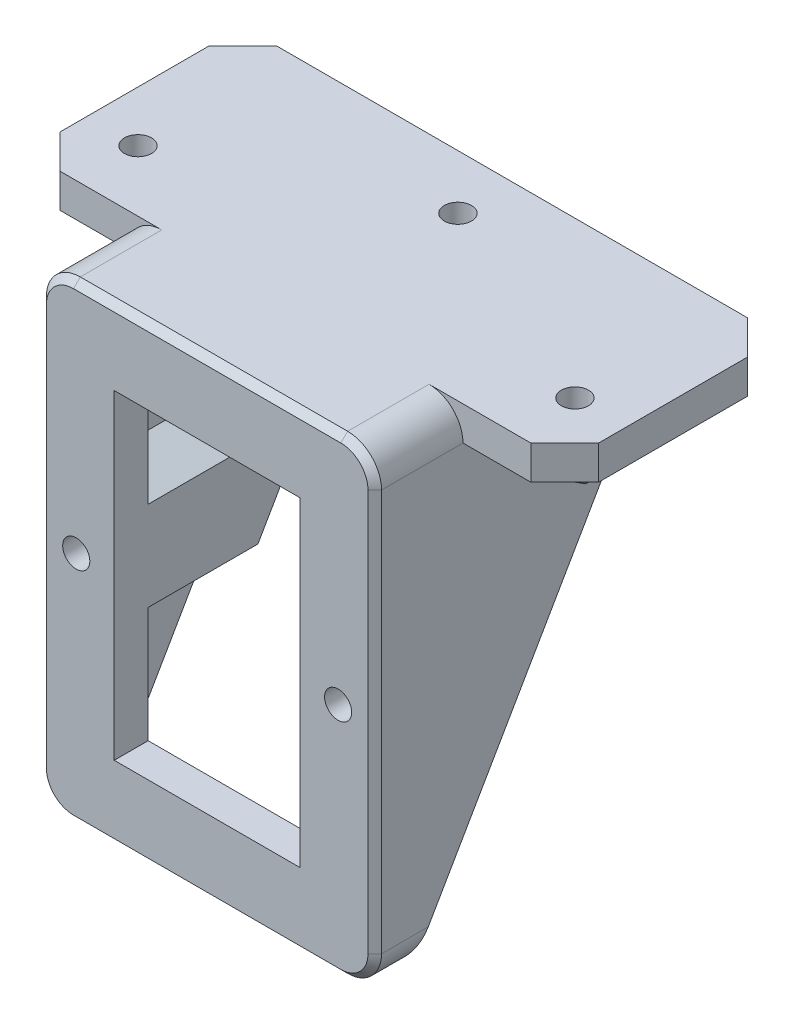
SolidWorks part; units mm, degrees
ref_plane "Front Plane" through (0, 0, 0) normal (0, 0, 1) x (1, 0, 0)
ref_plane "Top Plane" through (0, 0, 0) normal (0, 1, 0) x (1, 0, 0)
ref_plane "Right Plane" through (0, 0, 0) normal (1, 0, 0) x (0, 0, -1)
sketch "Sketch1" plane through (0, 0, 0) normal (0, 0, 1) x (1, 0, 0)
  line L0 (-36.4532, 0) -> (46.6601, 0) construction
  line L1 (-13.5, 23.4) -> (13.5, 23.4) construction
  line L2 (-13.5, 23.4) -> (-13.5, -23.4) construction
  line L3 (-13.5, -23.4) -> (13.5, -23.4) construction
  line L4 (13.5, 23.4) -> (13.5, -23.4) construction
  line L5 (0, 29.9068) -> (0, -40.6544) construction
  line L6 (-13.7, 23.6) -> (13.7, 23.6)
  line L7 (13.7, 23.6) -> (13.7, -23.6)
  line L8 (-13.7, -23.6) -> (13.7, -23.6)
  line L9 (-13.7, 23.6) -> (-13.7, -23.6)
  line L10 (-24.7, 34.6) -> (-24.7, -34.6)
  line L11 (-24.7, -34.6) -> (24.7, -34.6)
  line L12 (24.7, 34.6) -> (24.7, -34.6)
  line L13 (-24.7, 34.6) -> (24.7, 34.6)
  dimension "D1" = 46.8
  dimension "D2" = 27
  dimension "D3" = 0.2
  dimension "D4" = 11
extrude "Boss-Extrude1" add sketch "Sketch1" against normal blind 5
sketch "Sketch2" plane through (0, 0, 0) normal (0, 0, 1) x (1, 0, 0)
  line L0 (13.7, -23.6) -> (13.7, 23.6) construction
  line L1 (0, 0) -> (0, 17.0969) construction
  circle A0 centre (19.3, 0) radius 2
  circle A1 centre (-19.3, 0) radius 2
  dimension "D1" = 4
  dimension "D2" = 5.6
extrude "Cut-Extrude1" cut sketch "Sketch2" against normal blind 15
sketch "Sketch4" plane through (24.7, 0, 0) normal (1, 0, 0) x (0, 0, -1)
  line L0 (5, 34.6) -> (44.9526, 34.6)
  line L4 (44.9526, 34.6) -> (5, -34.6)
  line L5 (5, -34.6) -> (5, 34.6) construction
  line L6 (5, -34.6) -> (5, 34.6)
  line L7 (5, -34.6) -> (0, -34.6) construction
  dimension "D1" = 30
extrude "Boss-Extrude2" add sketch "Sketch4" against normal up to vertex (49.4 mm away)
sketch "Sketch3" plane through (0, 0, -5) normal (0, 0, -1) x (-1, 0, 0)
  line L1 (-19.3, -4.0415) -> (-15.8, -2.0207)
  line L2 (-15.8, -2.0207) -> (-15.8, 2.0207)
  line L3 (-15.8, 2.0207) -> (-19.3, 4.0415)
  line L4 (-19.3, 4.0415) -> (-22.8, 2.0207)
  line L5 (-22.8, 2.0207) -> (-22.8, -2.0207)
  line L6 (-22.8, -2.0207) -> (-19.3, -4.0415)
  line L7 (19.3, -4.0415) -> (22.8, -2.0207)
  line L8 (22.8, -2.0207) -> (22.8, 2.0207)
  line L9 (22.8, 2.0207) -> (19.3, 4.0415)
  line L10 (19.3, 4.0415) -> (15.8, 2.0207)
  line L11 (15.8, 2.0207) -> (15.8, -2.0207)
  line L12 (15.8, -2.0207) -> (19.3, -4.0415)
  circle A0 centre (-19.3, 0) radius 3.5 construction
  circle A1 centre (19.3, 0) radius 3.5 construction
  dimension "D1" = 7
extrude "Cut-Extrude2" cut sketch "Sketch3" along normal through all
sketch "Sketch5" plane through (0, 0, -5) normal (0, 0, 1) x (1, 0, 0)
  line L4 (-13.7, 23.6) -> (-13.7, -23.6)
  line L5 (-13.7, -23.6) -> (13.7, -23.6)
  line L6 (13.7, -23.6) -> (13.7, 23.6)
  line L7 (13.7, 23.6) -> (-13.7, 23.6)
  line L8 (-13.7, 23.6) -> (-13.7, -23.6)
  line L9 (-13.7, -23.6) -> (13.7, -23.6)
  line L10 (13.7, -23.6) -> (13.7, 23.6)
  line L11 (13.7, 23.6) -> (-13.7, 23.6)
  dimension "D1" = 0
extrude "Cut-Extrude3" cut sketch "Sketch5" against normal blind 93
sketch "Sketch6" plane through (0, 0, 0) normal (0, 0, 1) x (1, 0, 0)
  line L0 (19.7, 29.6) -> (-19.7, 29.6)
  line L1 (-19.7, 29.6) -> (-19.7, 10.0459)
  line L2 (-19.7, -34.6) -> (19.7, -34.6)
  line L3 (19.7, -34.6) -> (19.7, -10.0459)
  line L4 (24.7, 34.6) -> (-24.7, 34.6)
  line L5 (-24.7, 34.6) -> (-24.7, -34.6)
  line L6 (-24.7, -34.6) -> (24.7, -34.6)
  line L7 (24.7, -34.6) -> (24.7, 34.6)
  line L8 (24.7, 34.6) -> (-24.7, 34.6) construction
  line L10 (-24.7, -34.6) -> (24.7, -34.6) construction
  line L11 (24.7, -6.6973) -> (24.7, 34.6) construction
  line L12 (-15.8, -2.0207) -> (-19.3, -4.0415) construction
  line L13 (-19.3, -4.0415) -> (-22.8, -2.0207) construction
  line L14 (-22.8, -2.0207) -> (-22.8, 2.0207) construction
  line L15 (-22.8, 2.0207) -> (-19.3, 4.0415) construction
  line L16 (-19.3, 4.0415) -> (-15.8, 2.0207) construction
  line L17 (-15.8, 2.0207) -> (-15.8, -2.0207) construction
  line L18 (22.8, -2.0207) -> (19.3, -4.0415) construction
  line L19 (19.3, -4.0415) -> (15.8, -2.0207) construction
  line L20 (15.8, -2.0207) -> (15.8, 2.0207) construction
  line L21 (15.8, 2.0207) -> (19.3, 4.0415) construction
  line L22 (19.3, 4.0415) -> (22.8, 2.0207) construction
  line L23 (22.8, 2.0207) -> (22.8, -2.0207) construction
  line L24 (-15.8, -2.0207) -> (-19.3, -4.0415) construction
  line L25 (-19.3, -4.0415) -> (-22.8, -2.0207) construction
  line L26 (-22.8, -2.0207) -> (-22.8, 2.0207) construction
  line L27 (-22.8, 2.0207) -> (-19.3, 4.0415) construction
  line L28 (-19.3, 4.0415) -> (-15.8, 2.0207) construction
  line L29 (-15.8, 2.0207) -> (-15.8, -2.0207) construction
  line L30 (22.8, -2.0207) -> (19.3, -4.0415) construction
  line L31 (19.3, -4.0415) -> (15.8, -2.0207) construction
  line L32 (15.8, -2.0207) -> (15.8, 2.0207) construction
  line L33 (15.8, 2.0207) -> (19.3, 4.0415) construction
  line L34 (19.3, 4.0415) -> (22.8, 2.0207) construction
  line L35 (22.8, 2.0207) -> (22.8, -2.0207) construction
  line L36 (-19.7, 10.0459) -> (-10.8, 4.9075)
  line L37 (-10.8, 4.9075) -> (-10.8, -4.9075)
  line L38 (-10.8, -4.9075) -> (-19.7, -10.0459)
  line L39 (19.3, 9.815) -> (27.8, 4.9075) construction
  line L40 (19.7, 10.0459) -> (19.7, 29.6)
  line L41 (19.7, -29.6) -> (19.7, 29.6) construction
  line L42 (10.8, 4.9075) -> (19.7, 10.0459)
  line L43 (19.3, -9.815) -> (10.8, -4.9075) construction
  line L46 (19.7, -10.0459) -> (10.8, -4.9075)
  line L47 (10.8, -4.9075) -> (10.8, 4.9075)
  line L48 (-19.7, -10.0459) -> (-19.7, -34.6)
  line L49 (-19.7, 29.6) -> (-19.7, -29.6) construction
  line L50 (-10.8, -4.9075) -> (-19.3, -9.815) construction
  line L51 (-27.8, 4.9075) -> (-19.3, 9.815) construction
  line L52 (-19.3, 9.815) -> (-10.8, 4.9075) construction
  line L53 (-19.3, -9.815) -> (-27.8, -4.9075) construction
  line L54 (10.8, 4.9075) -> (19.3, 9.815) construction
  line L55 (-24.7, 34.6) -> (-24.7, -34.6) construction
  line L56 (-27.8, -4.9075) -> (-27.8, 4.9075) construction
  line L58 (27.8, -4.9075) -> (19.3, -9.815) construction
  line L60 (24.7, -34.6) -> (24.7, 34.6) construction
  line L61 (27.8, 4.9075) -> (27.8, -4.9075) construction
  line L62 (-19.7, -29.6) -> (19.7, -29.6) construction
  dimension "D1" = 0
  dimension "D2" = 5
  dimension "D3" = 5
  dimension "D4" = 5
extrude "Cut-Extrude4" cut sketch "Sketch6" against normal blind 93 from offset 5 offset against normal yes
sketch "Sketch7" plane through (0, 34.6, 0) normal (0, 1, 0) x (1, 0, 0)
  line L0 (24.7, 0) -> (-24.7, 0) construction
  line L1 (-39.7, 44.9526) -> (39.7, 44.9526)
  line L2 (-39.7, 44.9526) -> (-39.7, 0)
  line L3 (-39.7, 0) -> (39.7, 0)
  line L4 (39.7, 44.9526) -> (39.7, 0)
  line L5 (-24.7, 44.9526) -> (24.7, 44.9526) construction
  line L6 (-24.7, 44.9526) -> (-24.7, 0) construction
  line L8 (0, 0) -> (0, 55.3404) construction
  dimension "D1" = 15
extrude "Boss-Extrude3" add sketch "Sketch7" against normal blind 5
sketch "Sketch8" plane through (0, 29.6, 0) normal (0, -1, 0) x (1, 0, 0)
  line L1 (-3.5, -34.9319) -> (-3.5, -38.9734)
  line L2 (-3.5, -38.9734) -> (0, -40.9941)
  line L3 (0, -40.9941) -> (3.5, -38.9734)
  line L4 (3.5, -38.9734) -> (3.5, -34.9319)
  line L5 (3.5, -34.9319) -> (0, -32.9112)
  line L6 (0, -32.9112) -> (-3.5, -34.9319)
  line L7 (-32.2, -17.9585) -> (-35.7, -19.9793)
  line L8 (-35.7, -19.9793) -> (-35.7, -24.0207)
  line L9 (-35.7, -24.0207) -> (-32.2, -26.0415)
  line L10 (-32.2, -26.0415) -> (-28.7, -24.0207)
  line L11 (-28.7, -24.0207) -> (-28.7, -19.9793)
  line L12 (-28.7, -19.9793) -> (-32.2, -17.9585)
  line L13 (32.2, -17.9585) -> (28.7, -19.9793)
  line L14 (28.7, -19.9793) -> (28.7, -24.0207)
  line L15 (28.7, -24.0207) -> (32.2, -26.0415)
  line L16 (32.2, -26.0415) -> (35.7, -24.0207)
  line L17 (35.7, -24.0207) -> (35.7, -19.9793)
  line L18 (35.7, -19.9793) -> (32.2, -17.9585)
  line L30 (25.7, -25.7528) -> (32.2, -29.5056)
  line L31 (32.2, -29.5056) -> (38.7, -25.7528)
  line L32 (38.7, -25.7528) -> (38.7, -18.2472)
  line L33 (38.7, -18.2472) -> (32.2, -14.4944)
  line L34 (32.2, -14.4944) -> (25.7, -18.2472)
  line L35 (25.7, -18.2472) -> (25.7, -25.7528)
  line L36 (32.2, 0) -> (32.2, -44.9526) construction
  line L37 (24.7, 0) -> (39.7, 0) construction
  line L38 (39.7, -44.9526) -> (-39.7, -44.9526) construction
  line L39 (0, 0) -> (0, -56.5255) construction
  line L40 (-39.7, 0) -> (-24.7, 0) construction
  line L41 (-32.2, -14.4944) -> (-38.7, -18.2472)
  line L42 (-38.7, -18.2472) -> (-38.7, -25.7528)
  line L43 (-38.7, -25.7528) -> (-32.2, -29.5056)
  line L44 (-32.2, -29.5056) -> (-25.7, -25.7528)
  line L45 (-25.7, -25.7528) -> (-25.7, -18.2472)
  line L46 (-25.7, -18.2472) -> (-32.2, -14.4944)
  line L47 (0, -29.4471) -> (-6.5, -33.1999)
  line L48 (-6.5, -33.1999) -> (-6.5, -40.7054)
  line L49 (-6.5, -40.7054) -> (0, -44.4582)
  line L50 (0, -44.4582) -> (6.5, -40.7054)
  line L51 (6.5, -40.7054) -> (6.5, -33.1999)
  line L52 (6.5, -33.1999) -> (0, -29.4471)
  circle A0 centre (0, -36.9526) radius 3.5 construction
  circle A1 centre (-32.2, -22) radius 3.5 construction
  circle A2 centre (32.2, -22) radius 3.5 construction
  circle A3 centre (-32.2, -22) radius 6.5 construction
  circle A4 centre (0, -36.9526) radius 6.5 construction
  point P55 (-32.2, 0)
  dimension "D1" = 7
  dimension "D5" = 3
  dimension "D3" = 22
  dimension "D4" = 8
  dimension "D2" = 3
extrude "Boss-Extrude4" add sketch "Sketch8" along normal blind 3
sketch "Sketch9" plane through (0, 29.6, 0) normal (0, -1, 0) x (1, 0, 0)
  line L0 (3.5, -34.9319) -> (0, -32.9112) construction
  line L1 (0, -32.9112) -> (-3.5, -34.9319) construction
  line L2 (-3.5, -34.9319) -> (-3.5, -38.9734) construction
  line L3 (-3.5, -38.9734) -> (0, -40.9941) construction
  line L4 (0, -40.9941) -> (3.5, -38.9734) construction
  line L5 (3.5, -38.9734) -> (3.5, -34.9319) construction
  line L6 (35.7, -24.0207) -> (35.7, -19.9793)
  line L7 (35.7, -19.9793) -> (32.2, -17.9585)
  line L8 (32.2, -17.9585) -> (28.7, -19.9793)
  line L9 (28.7, -19.9793) -> (28.7, -24.0207)
  line L10 (28.7, -24.0207) -> (32.2, -26.0415)
  line L11 (32.2, -26.0415) -> (35.7, -24.0207)
  line L12 (35.7, -24.0207) -> (35.7, -19.9793)
  line L13 (35.7, -19.9793) -> (32.2, -17.9585)
  line L14 (32.2, -17.9585) -> (28.7, -19.9793)
  line L15 (28.7, -19.9793) -> (28.7, -24.0207)
  line L16 (28.7, -24.0207) -> (32.2, -26.0415)
  line L17 (32.2, -26.0415) -> (35.7, -24.0207)
  line L18 (-28.7, -24.0207) -> (-28.7, -19.9793) construction
  line L19 (-28.7, -19.9793) -> (-32.2, -17.9585) construction
  line L20 (-32.2, -17.9585) -> (-35.7, -19.9793) construction
  line L21 (-35.7, -19.9793) -> (-35.7, -24.0207) construction
  line L22 (-35.7, -24.0207) -> (-32.2, -26.0415) construction
  line L23 (-32.2, -26.0415) -> (-28.7, -24.0207) construction
  line L24 (3.5, -34.9319) -> (0, -32.9112)
  line L25 (0, -32.9112) -> (-3.5, -34.9319)
  line L26 (-3.5, -34.9319) -> (-3.5, -38.9734)
  line L27 (-3.5, -38.9734) -> (0, -40.9941)
  line L28 (0, -40.9941) -> (3.5, -38.9734)
  line L29 (3.5, -38.9734) -> (3.5, -34.9319)
  line L30 (-28.7, -24.0207) -> (-28.7, -19.9793)
  line L31 (-28.7, -19.9793) -> (-32.2, -17.9585)
  line L32 (-32.2, -17.9585) -> (-35.7, -19.9793)
  line L33 (-35.7, -19.9793) -> (-35.7, -24.0207)
  line L34 (-35.7, -24.0207) -> (-32.2, -26.0415)
  line L35 (-32.2, -26.0415) -> (-28.7, -24.0207)
  dimension "D1" = 0
extrude "Cut-Extrude5" cut sketch "Sketch9" against normal blind 1
sketch "Sketch10" plane through (0, 30.6, 0) normal (0, -1, 0) x (1, 0, 0)
  line L0 (24.7, 0) -> (39.7, 0) construction
  line L1 (-3.5, -34.9319) -> (-3.5, -38.9734) construction
  line L2 (-35.7, -19.9793) -> (-35.7, -24.0207) construction
  circle A0 centre (32.2, -22) radius 2
  circle A1 centre (0, -36.9526) radius 2
  circle A2 centre (-32.2, -22) radius 2
  point P4 (32.2, 0)
  point P9 (-3.5, -36.9526)
  point P16 (-35.7, -22)
  dimension "D1" = 4
  dimension "D2" = 22
extrude "Cut-Extrude6" cut sketch "Sketch10" against normal through all
sketch "Sketch11" plane through (0, 0, 0) normal (0, 0, 1) x (1, 0, 0)
  line L0 (39.7, 34.6) -> (-39.7, 34.6) construction
  line L1 (24.7, 29.6) -> (39.7, 29.6)
  line L2 (24.7, 29.6) -> (24.7, 34.6)
  line L3 (24.7, 34.6) -> (39.7, 34.6)
  line L4 (39.7, 29.6) -> (39.7, 34.6)
  line L5 (-24.7, 29.6) -> (-39.7, 29.6)
  line L6 (-24.7, 29.6) -> (-24.7, 34.6)
  line L7 (-24.7, 34.6) -> (-39.7, 34.6)
  line L8 (-39.7, 29.6) -> (-39.7, 34.6)
  line L9 (-39.7, 29.6) -> (-39.7, 34.6) construction
extrude "Cut-Extrude7" cut sketch "Sketch11" against normal blind 13
chamfer "Chamfer1" distance 2.75 angle 45 18 edges at (-25.7, 26.6, -22) (-28.95, 26.6, -27.6292) (-35.45, 26.6, -27.6292) (-38.7, 26.6, -22) (-35.45, 26.6, -16.3708) (-28.95, 26.6, -16.3708) (6.5, 26.6, -36.9526) (3.25, 26.6, -42.5818) (-3.25, 26.6, -42.5818) (-6.5, 26.6, -36.9526) (-3.25, 26.6, -31.3235) (3.25, 26.6, -31.3235) (28.95, 26.6, -16.3708) (35.45, 26.6, -16.3708) (38.7, 26.6, -22) (35.45, 26.6, -27.6292) (28.95, 26.6, -27.6292) (25.7, 26.6, -22)
sketch "Sketch12" plane through (0, 26.6, 0) normal (0, -1, 0) x (1, 0, 0)
  line L21 (3.5, -38.9734) -> (3.5, -34.9319) construction
  line L22 (3.5, -34.9319) -> (0, -32.9112) construction
  line L23 (0, -32.9112) -> (-3.5, -34.9319) construction
  line L24 (-3.5, -34.9319) -> (-3.5, -38.9734) construction
  line L25 (-3.5, -38.9734) -> (0, -40.9941) construction
  line L26 (0, -40.9941) -> (3.5, -38.9734) construction
  line L27 (35.45, -20.1236) -> (32.2, -18.2472)
  line L28 (32.2, -18.2472) -> (28.95, -20.1236)
  line L29 (28.95, -20.1236) -> (28.95, -23.8764)
  line L30 (28.95, -23.8764) -> (32.2, -25.7528)
  line L31 (35.45, -23.8764) -> (35.45, -20.1236)
  line L32 (32.2, -25.7528) -> (35.45, -23.8764)
  line L33 (35.45, -20.1236) -> (32.2, -18.2472)
  line L34 (32.2, -18.2472) -> (28.95, -20.1236)
  line L35 (28.95, -20.1236) -> (28.95, -23.8764)
  line L36 (28.95, -23.8764) -> (32.2, -25.7528)
  line L37 (35.45, -23.8764) -> (35.45, -20.1236)
  line L38 (32.2, -25.7528) -> (35.45, -23.8764)
  line L39 (32.2, -26.0415) -> (35.7, -24.0207)
  line L40 (35.7, -24.0207) -> (35.7, -19.9793)
  line L41 (35.7, -19.9793) -> (32.2, -17.9585)
  line L42 (32.2, -17.9585) -> (28.7, -19.9793)
  line L43 (28.7, -19.9793) -> (28.7, -24.0207)
  line L44 (28.7, -24.0207) -> (32.2, -26.0415)
  line L45 (32.2, -26.0415) -> (35.7, -24.0207)
  line L46 (35.7, -24.0207) -> (35.7, -19.9793)
  line L47 (35.7, -19.9793) -> (32.2, -17.9585)
  line L48 (32.2, -17.9585) -> (28.7, -19.9793)
  line L49 (28.7, -19.9793) -> (28.7, -24.0207)
  line L50 (28.7, -24.0207) -> (32.2, -26.0415)
  line L51 (-32.2, -26.0415) -> (-28.7, -24.0207) construction
  line L52 (-28.7, -24.0207) -> (-28.7, -19.9793) construction
  line L53 (-28.7, -19.9793) -> (-32.2, -17.9585) construction
  line L54 (-32.2, -17.9585) -> (-35.7, -19.9793) construction
  line L55 (-35.7, -19.9793) -> (-35.7, -24.0207) construction
  line L56 (-35.7, -24.0207) -> (-32.2, -26.0415) construction
  line L57 (3.5, -38.9734) -> (3.5, -34.9319)
  line L58 (3.5, -34.9319) -> (0, -32.9112)
  line L59 (0, -32.9112) -> (-3.5, -34.9319)
  line L60 (-3.5, -34.9319) -> (-3.5, -38.9734)
  line L61 (-3.5, -38.9734) -> (0, -40.9941)
  line L62 (0, -40.9941) -> (3.5, -38.9734)
  line L63 (-32.2, -26.0415) -> (-28.7, -24.0207)
  line L64 (-28.7, -24.0207) -> (-28.7, -19.9793)
  line L65 (-28.7, -19.9793) -> (-32.2, -17.9585)
  line L66 (-32.2, -17.9585) -> (-35.7, -19.9793)
  line L67 (-35.7, -19.9793) -> (-35.7, -24.0207)
  line L68 (-35.7, -24.0207) -> (-32.2, -26.0415)
  line L69 (-3.25, -38.829) -> (0, -40.7054)
  line L70 (0, -40.7054) -> (3.25, -38.829)
  line L71 (3.25, -38.829) -> (3.25, -35.0763)
  line L72 (3.25, -35.0763) -> (0, -33.1999)
  line L73 (0, -33.1999) -> (-3.25, -35.0763)
  line L74 (-3.25, -35.0763) -> (-3.25, -38.829)
  line L75 (-35.45, -23.8764) -> (-32.2, -25.7528)
  line L76 (-32.2, -25.7528) -> (-28.95, -23.8764)
  line L77 (-28.95, -23.8764) -> (-28.95, -20.1236)
  line L78 (-28.95, -20.1236) -> (-32.2, -18.2472)
  line L79 (-32.2, -18.2472) -> (-35.45, -20.1236)
  line L80 (-35.45, -20.1236) -> (-35.45, -23.8764)
  dimension "D1" = 0.25
  dimension "D2" = 0
  dimension "D3" = 0.25
  dimension "D4" = 0.25
extrude "Boss-Extrude5" add sketch "Sketch12" against normal blind 0.5
chamfer "Chamfer2" distance 0.25 angle 45 18 edges at (33.825, 26.6, -19.1854) (30.575, 26.6, -19.1854) (28.95, 26.6, -22) (30.575, 26.6, -24.8146) (33.825, 26.6, -24.8146) (35.45, 26.6, -22) (-33.825, 26.6, -24.8146) (-30.575, 26.6, -24.8146) (-28.95, 26.6, -22) (-30.575, 26.6, -19.1854) (-33.825, 26.6, -19.1854) (-35.45, 26.6, -22) (-1.625, 26.6, -39.7672) (1.625, 26.6, -39.7672) (3.25, 26.6, -36.9526) (1.625, 26.6, -34.1381) (-1.625, 26.6, -34.1381) (-3.25, 26.6, -36.9526)
fillet "Fillet1" radius 5 4 edges at (24.7, -34.6, -2.5) (-24.7, -34.6, -2.5) (-24.7, 34.6, -6.5) (24.7, 34.6, -6.5)
chamfer "Chamfer3" distance 1 angle 45 8 edges at (24.7, 0, 0) (0, -34.6, 0) (-24.7, 0, 0) (0, 34.6, 0) (-23.2355, -33.1355, 0) (-23.2355, 33.1355, 0) (23.2355, 33.1355, 0) (23.2355, -33.1355, 0)
chamfer "Chamfer4" distance 5 angle 45 4 edges at (-39.7, 32.1, -44.9526) (-39.7, 32.1, -13) (39.7, 32.1, -44.9526) (39.7, 32.1, -13)
equation "\"D5@Sketch8\"=\"D2@Sketch8\""
equation "\"D2@Sketch10\"=\"D3@Sketch8\""
equation "\"D4@Sketch12\"=\"D1@Sketch12\""
equation "\"D3@Sketch12\"=\"D1@Sketch12\""
